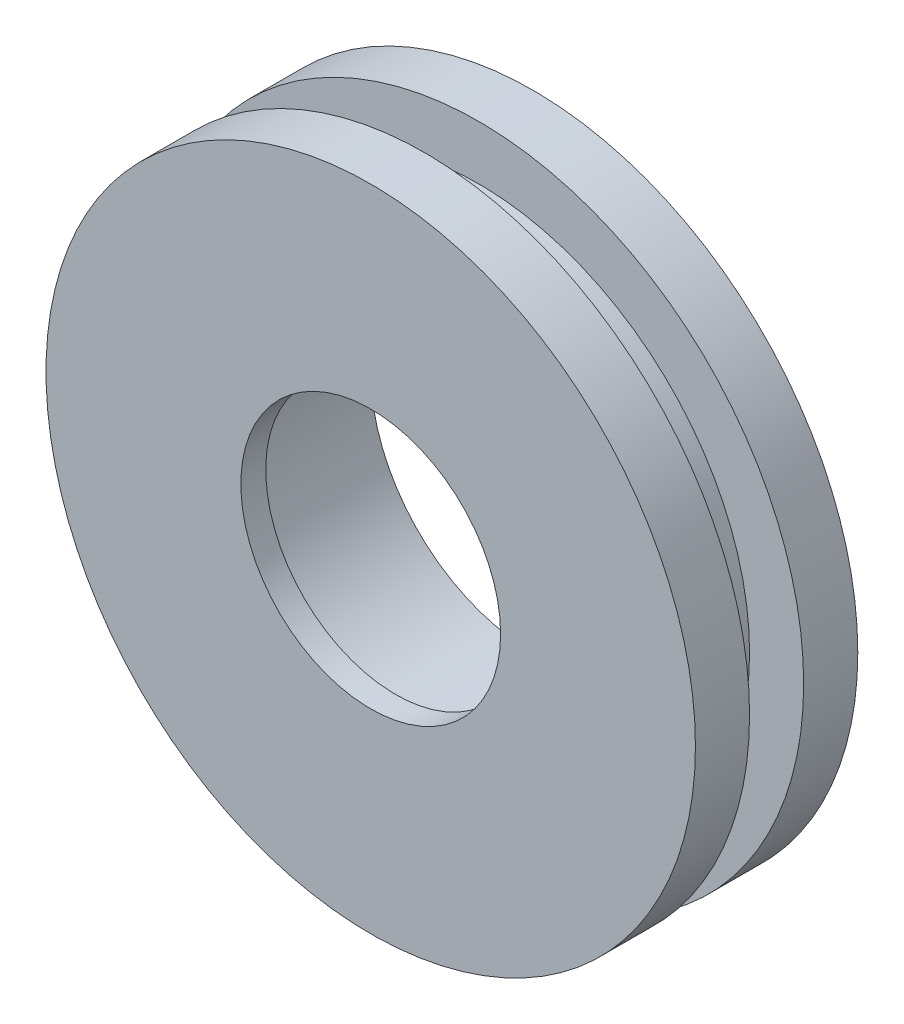
SolidWorks part; units mm, degrees
material "6061-T6 (SS)"
ref_plane "Front Plane" through (0, 0, 0) normal (0, 0, 1) x (1, 0, 0)
ref_plane "Top Plane" through (0, 0, 0) normal (0, 1, 0) x (1, 0, 0)
ref_plane "Right Plane" through (0, 0, 0) normal (1, 0, 0) x (0, 0, -1)
sketch "Sketch1" plane through (0, 0, 0) normal (1, 0, 0) x (0, 0, -1)
  line L0 (-9.1658, 0) -> (23.293, 0) construction
  line L1 (-2.3813, 9.525) -> (-2.3813, 3.81)
  line L2 (2.3813, 9.525) -> (0.7938, 9.525)
  line L3 (-2.3813, 9.525) -> (-0.7937, 9.525)
  line L4 (2.3813, 9.525) -> (2.3813, 4.7625)
  line L5 (-2.3813, 3.81) -> (-1.651, 3.81)
  line L6 (-1.651, 3.81) -> (-1.651, 4.7625)
  line L7 (-1.651, 4.7625) -> (2.3813, 4.7625)
  line L8 (-0.7937, 9.525) -> (-0.7937, 7.9375)
  line L9 (-0.7937, 7.9375) -> (0.7938, 7.9375)
  line L10 (0.7938, 7.9375) -> (0.7938, 9.525)
  line L11 (1.651, 4.7625) -> (1.651, 3.81) construction
  line L12 (-1.651, 3.81) -> (1.651, 3.81) construction
  point P2 (0, 7.9375)
  point P10 (0, 3.81)
  dimension "D1" = 1.5875
  dimension "D2" = 4.7625
  dimension "D3" = 9.525
  dimension "D4" = 19.05
  dimension "D5" = 7.62
  dimension "D6" = 3.302
  dimension "D7" = 1.5875
revolve "Revolve1" add sketch "Sketch1" angle 360 about L0
